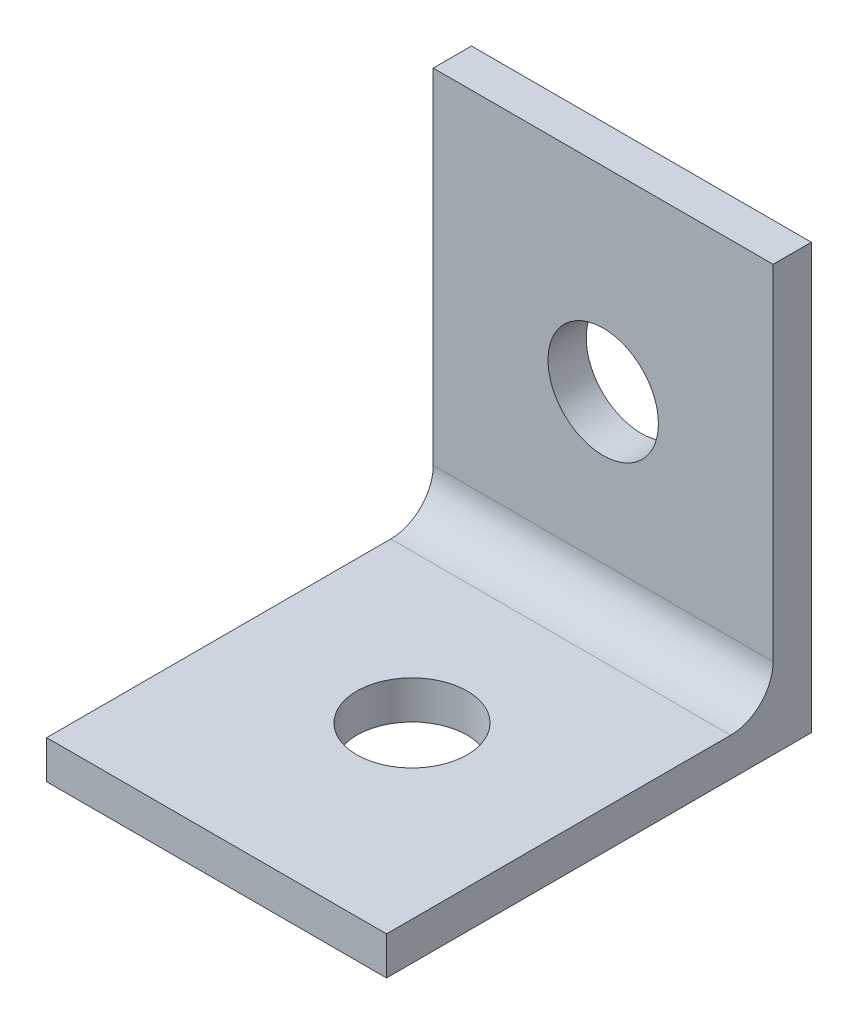
SolidWorks part; units mm, degrees
ref_plane "Front Plane" through (0, 0, 0) normal (0, 0, 1) x (1, 0, 0)
ref_plane "Top Plane" through (0, 0, 0) normal (0, 1, 0) x (1, 0, 0)
ref_plane "Right Plane" through (0, 0, 0) normal (1, 0, 0) x (0, 0, -1)
sketch "Sketch1" plane through (0, 0, 0) normal (0, 0, 1) x (1, 0, 0)
  line L1 (0, 0) -> (16, 0)
  line L2 (0, 0) -> (0, 20)
  line L3 (0, 20) -> (16, 20)
  line L4 (16, 0) -> (16, 20)
  dimension "D1" = 16
  dimension "D2" = 20
extrude "Boss-Extrude1" add sketch "Sketch1" along normal blind 1.8
sketch "Sketch2" plane through (0, 0, 0) normal (0, -1, 0) x (1, 0, 0)
  line L1 (0, 1.8) -> (16, 1.8)
  line L2 (0, 1.8) -> (0, 20)
  line L3 (0, 20) -> (16, 20)
  line L4 (16, 1.8) -> (16, 20)
  dimension "D1" = 18.2
  dimension "D2" = 16
extrude "Boss-Extrude2" add sketch "Sketch2" against normal blind 1.8
sketch "Sketch3" plane through (0, 0, 1.8) normal (0, 0, 1) x (1, 0, 0)
  line L0 (16, 1.8) -> (16, 20) construction
  line L1 (0, 1.8) -> (16, 1.8) construction
  circle A0 centre (8, 10.8) radius 2.6
  dimension "D1" = 5.2
  dimension "D2" = 8
  dimension "D3" = 9
extrude "Cut-Extrude1" cut sketch "Sketch3" against normal blind 1.8
sketch "Sketch4" plane through (0, 1.8, 0) normal (0, 1, 0) x (1, 0, 0)
  line L0 (16, -1.8) -> (16, -20) construction
  line L2 (16, -1.8) -> (0, -1.8) construction
  circle A0 centre (8, -10.8) radius 2.6
  dimension "D1" = 8
  dimension "D2" = 5.2
  dimension "D3" = 9
extrude "Cut-Extrude2" cut sketch "Sketch4" against normal blind 1.8
fillet "Fillet1" radius 2 1 edges at (8, 1.8, 1.8)
